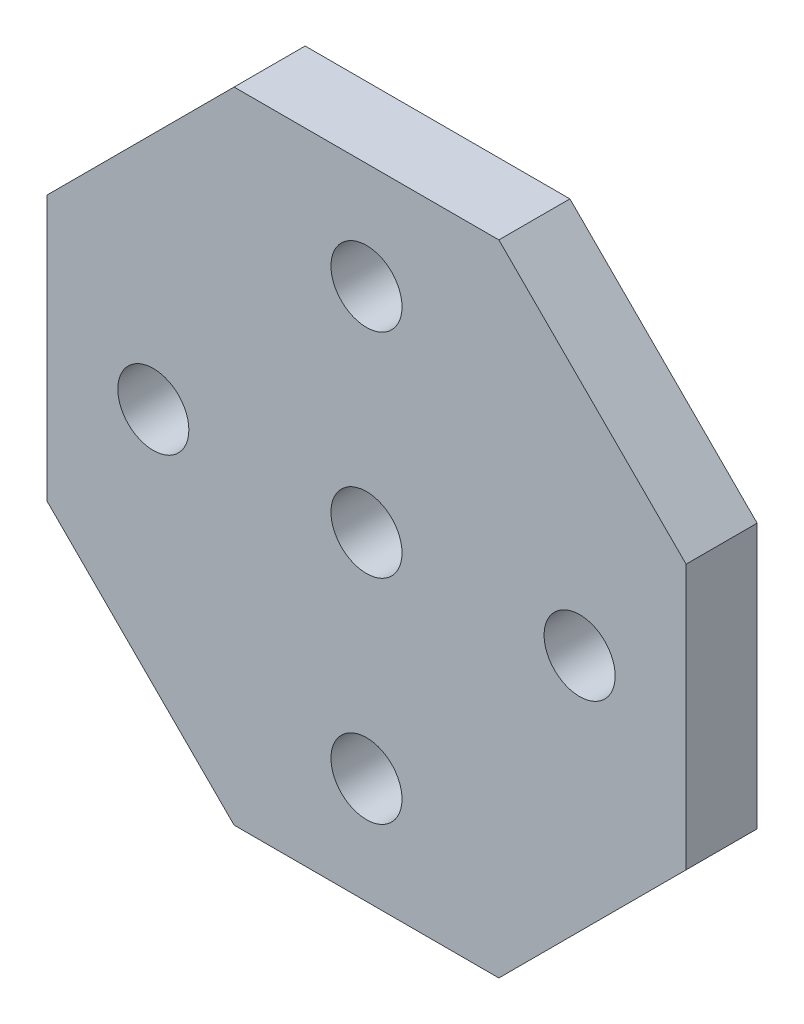
SolidWorks part; units mm, degrees
ref_plane "Alzado" through (0, 0, 0) normal (0, 0, 1) x (1, 0, 0)
ref_plane "Planta" through (0, 0, 0) normal (0, 1, 0) x (1, 0, 0)
ref_plane "Vista lateral" through (0, 0, 0) normal (1, 0, 0) x (0, 0, -1)
sketch "Model" plane through (0, 0, 0) normal (0, 0, 1) x (1, 0, 0)
  line L0 (221.3376, 228.457) -> (210.158, 228.457)
  line L1 (210.158, 255.447) -> (221.3376, 255.447)
  line L2 (210.158, 228.457) -> (202.2528, 236.3622)
  line L3 (202.2528, 236.3622) -> (202.2528, 247.5418)
  line L4 (202.2528, 247.5418) -> (210.158, 255.447)
  line L5 (229.2428, 236.3622) -> (221.3376, 228.457)
  line L6 (221.3376, 255.447) -> (229.2428, 247.5418)
  line L7 (229.2428, 247.5418) -> (229.2428, 236.3622)
  circle A0 centre (215.7478, 241.952) radius 1.5
  circle A1 centre (215.7478, 232.952) radius 1.5
  circle A2 centre (215.7478, 250.952) radius 1.5
  circle A3 centre (224.7478, 241.952) radius 1.5
  circle A4 centre (206.7478, 241.952) radius 1.5
extrude "Saliente-Extruir1" add sketch "Model" along normal blind 3
